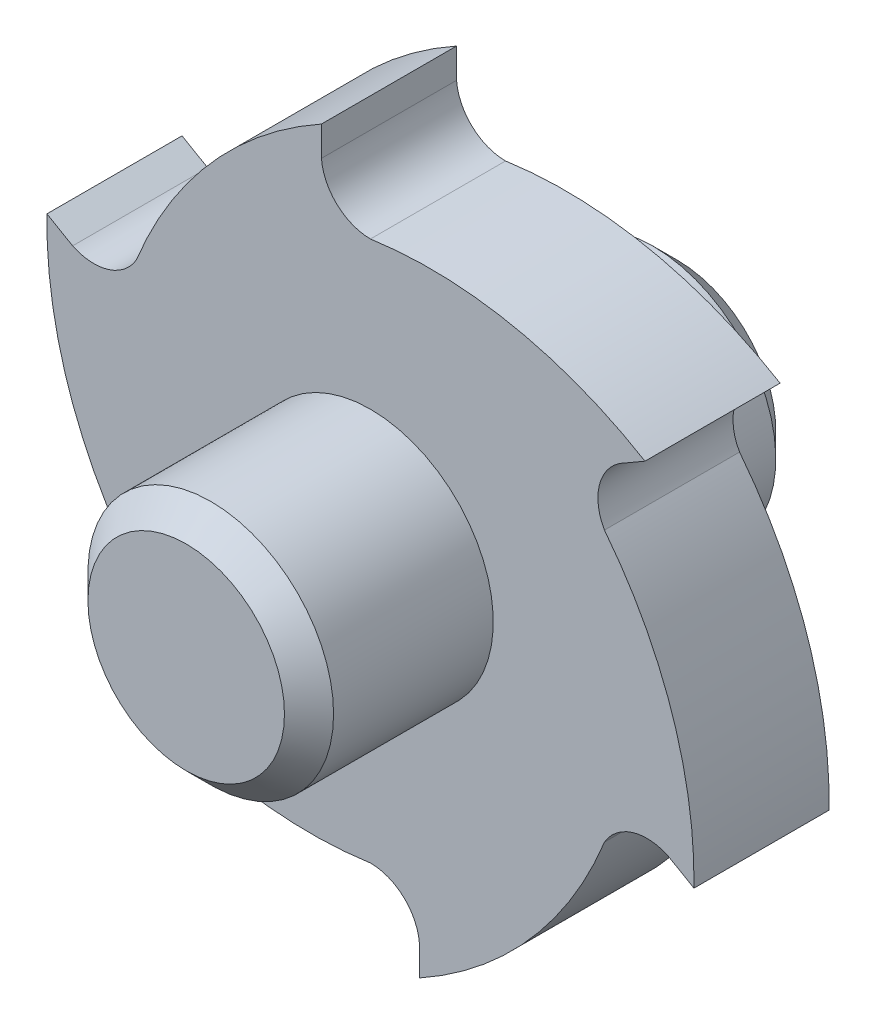
SolidWorks part; units mm, degrees
ref_plane "前基準面" through (0, 0, 0) normal (0, 0, 1) x (1, 0, 0)
ref_plane "上基準面" through (0, 0, 0) normal (0, 1, 0) x (1, 0, 0)
ref_plane "右基準面" through (0, 0, 0) normal (1, 0, 0) x (0, 0, -1)
sketch "草圖3" plane through (0, 0, 0) normal (1, 0, 0) x (0, 0, -1)
  line L0 (0, 0) -> (15, 0)
  line L1 (15, 0) -> (15, 20)
  line L2 (15, 20) -> (26, 20)
  line L3 (26, 20) -> (26, 0)
  line L4 (26, 0) -> (40, 0)
  line L5 (40, 0) -> (40, -10)
  line L6 (40, -10) -> (0, -10)
  line L7 (0, -10) -> (0, 0)
  point P3 (23.4229, 0)
  dimension "D1" = 40
  dimension "D2" = 10
  dimension "D3" = 30
  dimension "D4" = 15
  dimension "D5" = 14
revolve "旋轉1" add sketch "草圖3" angle 360 about L6
sketch "草圖4" plane through (0, 0, -26) normal (0, 0, -1) x (-1, 0, 0)
  circle A0 centre (0, -10) radius 13.5
  dimension "D1" = 27
extrude "填料-伸長1" add sketch "草圖4" along normal blind 1
chamfer "導角1" distance 2 angle 45 2 edges at (0, 0, 0) (0, 0, -40)
sketch "草圖1" plane through (0, 0, 0) normal (0, 0, 1) x (1, 0, 0)
  line L0 (0, -10) -> (0, 20) construction
  line L1 (0, -10) -> (42.9246, 14.7826) construction
  line L2 (-3.9881, 15.6923) -> (-3.9881, 19.7337)
  line L3 (20.2486, 6.3093) -> (23.7488, 8.3302) construction
  line L4 (-2, -6.5359) -> (40.9246, 18.2467) construction
  line L5 (0, 20) -> (31.5023, 20) construction
  arc A0 (25.9808, 5) -> (-3.9881, 19.7337) centre (0, -10) ccw
  arc A2 (22.5167, 3) -> (-3.9881, 15.6923) centre (0, -10) ccw construction
  arc A3 (-3.9881, 15.6923) -> (0, 12) centre (0, 16) ccw
  arc A4 (0, 12) -> (25.9808, 5) centre (4.8671, -21.6498) cw
  point P49 (0, -10)
  dimension "D1" = 60
  dimension "D4" = 8
  dimension "D6" = 34
  dimension "D2" = 60
  dimension "D5" = 4
extrude "除料-伸長1" cut sketch "草圖1" against normal through all
pattern_circular "環狀複製排列1" count 6 every 60 about axis through (0, -10, 0) along (0, 0, 1) of "除料-伸長1"
